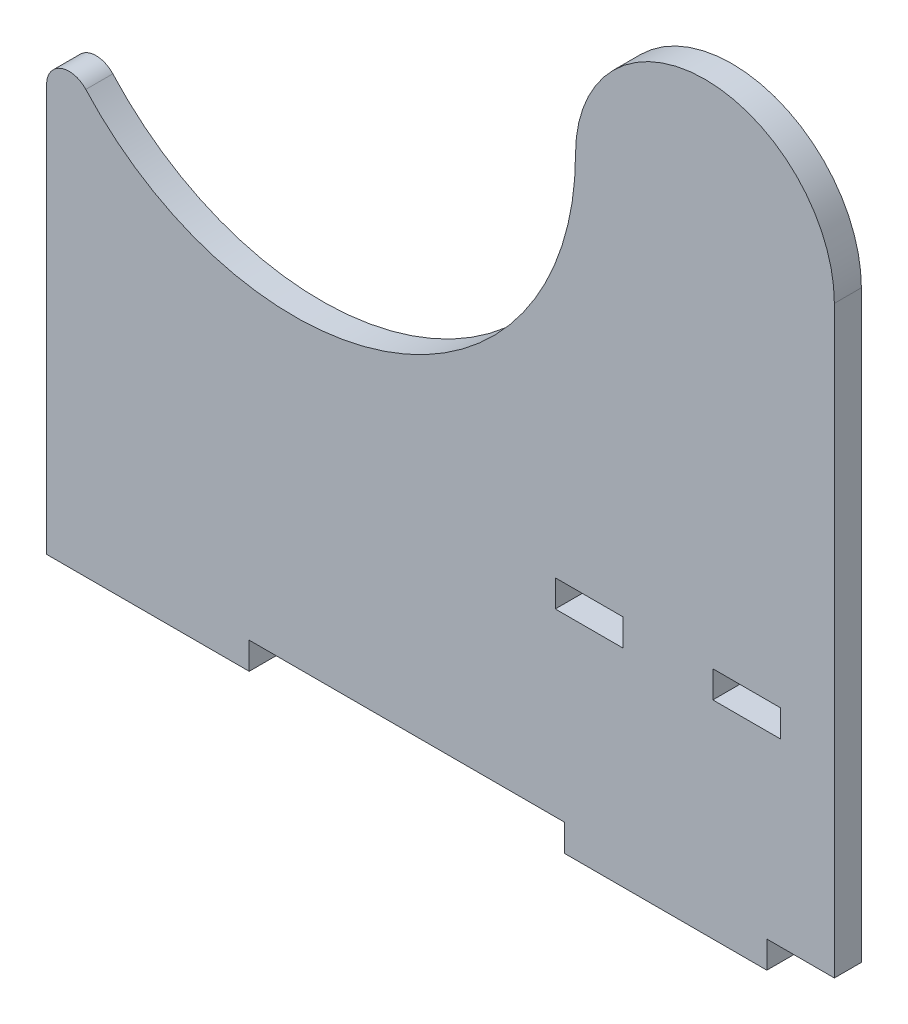
SolidWorks part; units mm, degrees
ref_plane "Front Plane" through (0, 0, 0) normal (0, 0, 1) x (1, 0, 0)
ref_plane "Top Plane" through (0, 0, 0) normal (0, 1, 0) x (1, 0, 0)
ref_plane "Right Plane" through (0, 0, 0) normal (1, 0, 0) x (0, 0, -1)
sketch "Sketch1" plane through (0, 0, 0) normal (0, 0, 1) x (1, 0, 0)
  line L0 (105.0015, -129.7919) -> (120.0015, -129.7919)
  line L3 (60.0015, -129.7919) -> (-9.9985, -129.7919)
  line L4 (-54.9985, -29.6886) -> (-54.9985, -129.7919)
  line L6 (-54.9985, -129.7919) -> (-54.9985, -135.7919)
  line L7 (-54.9985, -135.7919) -> (-9.9985, -135.7919)
  line L8 (-9.9985, -129.7919) -> (-9.9985, -135.7919)
  line L14 (105.0015, -129.7919) -> (105.0015, -135.7919)
  line L15 (105.0015, -135.7919) -> (60.0015, -135.7919)
  line L16 (60.0015, -129.7919) -> (60.0015, -135.7919)
  line L17 (120.0015, -129.7919) -> (120.0015, 0)
  arc A0 (-54.9985, -29.6886) -> (62.5, 0) centre (0, 0) ccw
  arc A2 (62.5, 0) -> (120.0015, 0) centre (91.2508, 0) cw
  dimension "D1" = 125
  dimension "D3" = 175
  dimension "D4" = 45
  dimension "D5" = 6
  dimension "D7" = 6
  dimension "D8" = 45
extrude "Boss-Extrude1" add sketch "Sketch1" along normal blind 6
sketch "Sketch2" plane through (0, 0, 6) normal (0, 0, 1) x (1, 0, 0)
  line L0 (-9.9985, -129.7919) -> (60.0015, -129.7919) construction
  line L1 (108.0015, -83.7919) -> (93.0015, -83.7919)
  line L2 (108.0015, -83.7919) -> (108.0015, -89.7919)
  line L3 (108.0015, -89.7919) -> (93.0015, -89.7919)
  line L4 (93.0015, -83.7919) -> (93.0015, -89.7919)
  line L5 (73.0015, -83.7919) -> (58.0015, -83.7919)
  line L6 (73.0015, -83.7919) -> (73.0015, -89.7919)
  line L7 (73.0015, -89.7919) -> (58.0015, -89.7919)
  line L8 (58.0015, -83.7919) -> (58.0015, -89.7919)
  line L9 (58.0015, -83.7919) -> (73.0015, -83.7919)
  line L10 (58.0015, -83.7919) -> (58.0015, -89.7919)
  line L11 (58.0015, -89.7919) -> (73.0015, -89.7919)
  line L12 (108.0015, -83.7919) -> (108.0015, -89.7919)
  line L13 (93.0015, -83.7919) -> (108.0015, -83.7919)
  line L14 (93.0015, -89.7919) -> (108.0015, -89.7919)
  line L15 (120.0015, -129.7919) -> (120.0015, 0) construction
  line L16 (58.0015, -83.7919) -> (108.0015, -83.7919)
  line L17 (58.0015, -83.7919) -> (58.0015, -89.7919)
  line L18 (58.0015, -89.7919) -> (108.0015, -89.7919)
  line L19 (108.0015, -83.7919) -> (108.0015, -89.7919)
  point P8 (108.0015, -86.7919)
  dimension "D1" = 6
  dimension "D2" = 50
  dimension "D3" = 15
  dimension "D4" = 15
  dimension "D5" = 40
  dimension "D6" = 50
  dimension "D7" = 12
extrude "Cut-Extrude1" cut sketch "Sketch2" against normal blind 10 contours L5 L8 L7 L6 | L1 L4 L3 L2
fillet "Fillet1" radius 5 1 edges at (-54.9985, -29.6886, 3)
